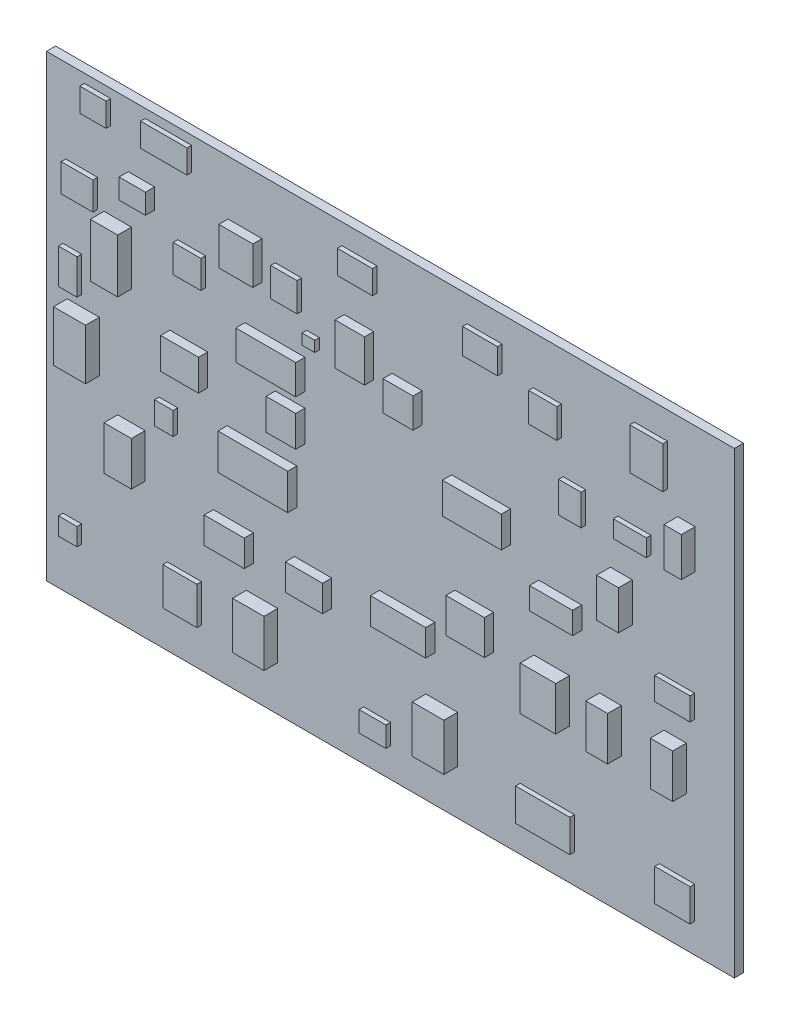
SolidWorks part; units mm, degrees
ref_plane "Front" through (0, 0, 0) normal (0, 0, 1) x (1, 0, 0)
ref_plane "Top" through (0, 0, 0) normal (0, 1, 0) x (1, 0, 0)
ref_plane "Right" through (0, 0, 0) normal (1, 0, 0) x (0, 0, -1)
sketch "Sketch1" plane through (0, 0, 0) normal (0, 0, 1) x (1, 0, 0)
  line L1 (-750, 500) -> (750, 500)
  line L2 (-750, 500) -> (-750, -500)
  line L3 (-750, -500) -> (750, -500)
  line L4 (750, 500) -> (750, -500)
  line L5 (-750, 500) -> (750, -500) construction
  line L6 (-750, -500) -> (750, 500) construction
  point P0 (0, 0)
  dimension "D1" = 1000
  dimension "D2" = 1500
extrude "Boss-Extrude1" add sketch "Sketch1" along normal blind 20
sketch "Sketch3" plane through (0, 0, 20) normal (0, 0, 1) x (1, 0, 0)
  line L1 (-317.0383, 203.9602) -> (-186.4548, 203.9602)
  line L2 (-317.0383, 203.9602) -> (-317.0383, 139.0841)
  line L3 (-317.0383, 139.0841) -> (-186.4548, 139.0841)
  line L4 (-186.4548, 203.9602) -> (-186.4548, 139.0841)
  line L5 (-317.0383, 203.9602) -> (-186.4548, 139.0841) construction
  line L6 (-317.0383, 139.0841) -> (-186.4548, 203.9602) construction
  line L7 (-355.9265, -9.9808) -> (-204.0397, -9.9808)
  line L8 (-355.9265, -9.9808) -> (-355.9265, -88.3609)
  line L9 (-355.9265, -88.3609) -> (-204.0397, -88.3609)
  line L10 (-204.0397, -9.9808) -> (-204.0397, -88.3609)
  line L11 (-355.9265, -9.9808) -> (-204.0397, -88.3609) construction
  line L12 (-355.9265, -88.3609) -> (-204.0397, -9.9808) construction
  line L13 (-571.6187, 361.8722) -> (-514.0837, 361.8722)
  line L14 (-571.6187, 361.8722) -> (-571.6187, 318.1665)
  line L15 (-571.6187, 318.1665) -> (-514.0837, 318.1665)
  line L16 (-514.0837, 361.8722) -> (-514.0837, 318.1665)
  line L17 (-571.6187, 361.8722) -> (-514.0837, 318.1665) construction
  line L18 (-571.6187, 318.1665) -> (-514.0837, 361.8722) construction
  line L19 (-354.0935, 381.1909) -> (-279.9831, 381.1909)
  line L20 (-354.0935, 381.1909) -> (-354.0935, 298.8478)
  line L21 (-354.0935, 298.8478) -> (-279.9831, 298.8478)
  line L22 (-279.9831, 381.1909) -> (-279.9831, 298.8478)
  line L23 (-354.0935, 381.1909) -> (-279.9831, 298.8478) construction
  line L24 (-354.0935, 298.8478) -> (-279.9831, 381.1909) construction
  line L25 (-251.1089, 107.9296) -> (-186.4548, 107.9296)
  line L26 (-251.1089, 107.9296) -> (-251.1089, 40.1021)
  line L27 (-251.1089, 40.1021) -> (-186.4548, 40.1021)
  line L28 (-186.4548, 107.9296) -> (-186.4548, 40.1021)
  line L29 (-251.1089, 107.9296) -> (-186.4548, 40.1021) construction
  line L30 (-251.1089, 40.1021) -> (-186.4548, 107.9296) construction
  line L31 (-100.7834, 327.4037) -> (-36.4863, 327.4037)
  line L32 (-100.7834, 327.4037) -> (-100.7834, 236.3285)
  line L33 (-100.7834, 236.3285) -> (-36.4863, 236.3285)
  line L34 (-36.4863, 327.4037) -> (-36.4863, 236.3285)
  line L35 (-100.7834, 327.4037) -> (-36.4863, 236.3285) construction
  line L36 (-100.7834, 236.3285) -> (-36.4863, 327.4037) construction
  line L37 (3.7883, 268.6967) -> (69.2703, 268.6967)
  line L38 (3.7883, 268.6967) -> (3.7883, 203.9602)
  line L39 (3.7883, 203.9602) -> (69.2703, 203.9602)
  line L40 (69.2703, 268.6967) -> (69.2703, 203.9602)
  line L41 (3.7883, 268.6967) -> (69.2703, 203.9602) construction
  line L42 (3.7883, 203.9602) -> (69.2703, 268.6967) construction
  line L43 (-480.9938, 107.9296) -> (-398.4458, 107.9296)
  line L44 (-480.9938, 107.9296) -> (-480.9938, 40.1021)
  line L45 (-480.9938, 40.1021) -> (-398.4458, 40.1021)
  line L46 (-398.4458, 107.9296) -> (-398.4458, 40.1021)
  line L47 (-480.9938, 107.9296) -> (-398.4458, 40.1021) construction
  line L48 (-480.9938, 40.1021) -> (-398.4458, 107.9296) construction
  line L49 (-386.1582, -183.6237) -> (-298.6708, -183.6237)
  line L50 (-386.1582, -183.6237) -> (-386.1582, -241.3069)
  line L51 (-386.1582, -241.3069) -> (-298.6708, -241.3069)
  line L52 (-298.6708, -183.6237) -> (-298.6708, -241.3069)
  line L53 (-386.1582, -183.6237) -> (-298.6708, -241.3069) construction
  line L54 (-386.1582, -241.3069) -> (-298.6708, -183.6237) construction
  line L55 (-209.0077, -183.6237) -> (-128.0535, -183.6237)
  line L56 (-209.0077, -183.6237) -> (-209.0077, -241.3069)
  line L57 (-209.0077, -241.3069) -> (-128.0535, -241.3069)
  line L58 (-128.0535, -183.6237) -> (-128.0535, -241.3069)
  line L59 (-209.0077, -183.6237) -> (-128.0535, -241.3069) construction
  line L60 (-209.0077, -241.3069) -> (-128.0535, -183.6237) construction
  line L61 (-23.8058, -154.7821) -> (96.8644, -154.7821)
  line L62 (-23.8058, -154.7821) -> (-23.8058, -212.4653)
  line L63 (-23.8058, -212.4653) -> (96.8644, -212.4653)
  line L64 (96.8644, -154.7821) -> (96.8644, -212.4653)
  line L65 (-23.8058, -154.7821) -> (96.8644, -212.4653) construction
  line L66 (-23.8058, -212.4653) -> (96.8644, -154.7821) construction
  line L67 (140.84, -72.08) -> (224.8272, -72.08)
  line L68 (140.84, -72.08) -> (140.84, -147.6702)
  line L69 (140.84, -147.6702) -> (224.8272, -147.6702)
  line L70 (224.8272, -72.08) -> (224.8272, -147.6702)
  line L71 (140.84, -72.08) -> (224.8272, -147.6702) construction
  line L72 (140.84, -147.6702) -> (224.8272, -72.08) construction
  line L73 (133.3998, 141.8434) -> (261.7349, 141.8434)
  line L74 (133.3998, 141.8434) -> (133.3998, 74.0159)
  line L75 (133.3998, 74.0159) -> (261.7349, 74.0159)
  line L76 (261.7349, 141.8434) -> (261.7349, 74.0159)
  line L77 (133.3998, 141.8434) -> (261.7349, 74.0159) construction
  line L78 (133.3998, 74.0159) -> (261.7349, 141.8434) construction
  line L79 (323.3608, 37.9257) -> (417.2566, 37.9257)
  line L80 (323.3608, 37.9257) -> (323.3608, -9.9808)
  line L81 (323.3608, -9.9808) -> (417.2566, -9.9808)
  line L82 (417.2566, 37.9257) -> (417.2566, -9.9808)
  line L83 (323.3608, 37.9257) -> (417.2566, -9.9808) construction
  line L84 (323.3608, -9.9808) -> (417.2566, 37.9257) construction
  point P0 (-251.7466, 171.5221)
  point P5 (-279.9831, -49.1709)
  point P10 (-542.8512, 340.0193)
  point P15 (-317.0383, 340.0193)
  point P20 (-218.7819, 74.0159)
  point P25 (-68.6349, 281.8661)
  point P30 (36.5293, 236.3285)
  point P35 (-439.7198, 74.0159)
  point P40 (-342.4145, -212.4653)
  point P45 (-168.5306, -212.4653)
  point P50 (36.5293, -183.6237)
  point P55 (182.8336, -109.8751)
  point P60 (197.5674, 107.9296)
  point P65 (370.3087, 13.9724)
extrude "Boss-Extrude3" add sketch "Sketch3" along normal blind 20
sketch "Sketch4" plane through (0, 0, 20) normal (0, 0, 1) x (1, 0, 0)
  line L1 (-463.823, 287.2753) -> (-403.3178, 287.2753)
  line L2 (-463.823, 287.2753) -> (-463.823, 226.4325)
  line L3 (-463.823, 226.4325) -> (-403.3178, 226.4325)
  line L4 (-403.3178, 287.2753) -> (-403.3178, 226.4325)
  line L5 (-463.823, 287.2753) -> (-403.3178, 226.4325) construction
  line L6 (-463.823, 226.4325) -> (-403.3178, 287.2753) construction
  line L7 (-105.8832, 455.092) -> (-29.1701, 455.092)
  line L8 (-105.8832, 455.092) -> (-105.8832, 403.7369)
  line L9 (-105.8832, 403.7369) -> (-29.1701, 403.7369)
  line L10 (-29.1701, 455.092) -> (-29.1701, 403.7369)
  line L11 (-105.8832, 455.092) -> (-29.1701, 403.7369) construction
  line L12 (-105.8832, 403.7369) -> (-29.1701, 455.092) construction
  line L13 (-251.2508, 350.1229) -> (-193.5545, 350.1229)
  line L14 (-251.2508, 350.1229) -> (-251.2508, 287.2753)
  line L15 (-251.2508, 287.2753) -> (-193.5545, 287.2753)
  line L16 (-193.5545, 350.1229) -> (-193.5545, 287.2753)
  line L17 (-251.2508, 350.1229) -> (-193.5545, 287.2753) construction
  line L18 (-251.2508, 287.2753) -> (-193.5545, 350.1229) construction
  line L19 (167.2364, 444.0695) -> (243.4631, 444.0695)
  line L20 (167.2364, 444.0695) -> (167.2364, 388.8199)
  line L21 (167.2364, 388.8199) -> (243.4631, 388.8199)
  line L22 (243.4631, 444.0695) -> (243.4631, 388.8199)
  line L23 (167.2364, 444.0695) -> (243.4631, 388.8199) construction
  line L24 (167.2364, 388.8199) -> (243.4631, 444.0695) construction
  line L25 (311.388, 395.4244) -> (372.7703, 395.4244)
  line L26 (311.388, 395.4244) -> (311.388, 331.6449)
  line L27 (311.388, 331.6449) -> (372.7703, 331.6449)
  line L28 (372.7703, 395.4244) -> (372.7703, 331.6449)
  line L29 (311.388, 395.4244) -> (372.7703, 331.6449) construction
  line L30 (311.388, 331.6449) -> (372.7703, 395.4244) construction
  line L31 (531.9625, 440.7258) -> (603.8475, 440.7258)
  line L32 (531.9625, 440.7258) -> (531.9625, 350.1229)
  line L33 (531.9625, 350.1229) -> (603.8475, 350.1229)
  line L34 (603.8475, 440.7258) -> (603.8475, 350.1229)
  line L35 (531.9625, 440.7258) -> (603.8475, 350.1229) construction
  line L36 (531.9625, 350.1229) -> (603.8475, 440.7258) construction
  line L37 (496.0199, 245.2414) -> (567.905, 245.2414)
  line L38 (496.0199, 245.2414) -> (496.0199, 207.6237)
  line L39 (496.0199, 207.6237) -> (567.905, 207.6237)
  line L40 (567.905, 245.2414) -> (567.905, 207.6237)
  line L41 (496.0199, 245.2414) -> (567.905, 207.6237) construction
  line L42 (496.0199, 207.6237) -> (567.905, 245.2414) construction
  line L43 (376.7873, 260.125) -> (425.6283, 260.125)
  line L44 (376.7873, 260.125) -> (376.7873, 192.74)
  line L45 (376.7873, 192.74) -> (425.6283, 192.74)
  line L46 (425.6283, 260.125) -> (425.6283, 192.74)
  line L47 (376.7873, 260.125) -> (425.6283, 192.74) construction
  line L48 (376.7873, 192.74) -> (425.6283, 260.125) construction
  line L49 (-504.3705, -30.1978) -> (-463.823, -30.1978)
  line L50 (-504.3705, -30.1978) -> (-504.3705, -79.5906)
  line L51 (-504.3705, -79.5906) -> (-463.823, -79.5906)
  line L52 (-463.823, -30.1978) -> (-463.823, -79.5906)
  line L53 (-504.3705, -30.1978) -> (-463.823, -79.5906) construction
  line L54 (-504.3705, -79.5906) -> (-463.823, -30.1978) construction
  line L55 (-708.0551, 317.6968) -> (-638.6656, 317.6968)
  line L56 (-708.0551, 317.6968) -> (-708.0551, 256.8539)
  line L57 (-708.0551, 256.8539) -> (-638.6656, 256.8539)
  line L58 (-638.6656, 317.6968) -> (-638.6656, 256.8539)
  line L59 (-708.0551, 317.6968) -> (-638.6656, 256.8539) construction
  line L60 (-708.0551, 256.8539) -> (-638.6656, 317.6968) construction
  line L61 (-667.2335, 480.7695) -> (-610.0977, 480.7695)
  line L62 (-667.2335, 480.7695) -> (-667.2335, 429.4144)
  line L63 (-667.2335, 429.4144) -> (-610.0977, 429.4144)
  line L64 (-610.0977, 480.7695) -> (-610.0977, 429.4144)
  line L65 (-667.2335, 480.7695) -> (-610.0977, 429.4144) construction
  line L66 (-667.2335, 429.4144) -> (-610.0977, 480.7695) construction
  line L67 (-534.6232, 480.7695) -> (-433.5704, 480.7695)
  line L68 (-534.6232, 480.7695) -> (-534.6232, 429.4144)
  line L69 (-534.6232, 429.4144) -> (-433.5704, 429.4144)
  line L70 (-433.5704, 480.7695) -> (-433.5704, 429.4144)
  line L71 (-534.6232, 480.7695) -> (-433.5704, 429.4144) construction
  line L72 (-534.6232, 429.4144) -> (-433.5704, 480.7695) construction
  line L73 (-713.8763, 155.3115) -> (-673.3604, 155.3115)
  line L74 (-713.8763, 155.3115) -> (-713.8763, 78.9005)
  line L75 (-713.8763, 78.9005) -> (-673.3604, 78.9005)
  line L76 (-673.3604, 155.3115) -> (-673.3604, 78.9005)
  line L77 (-713.8763, 155.3115) -> (-673.3604, 78.9005) construction
  line L78 (-713.8763, 78.9005) -> (-673.3604, 155.3115) construction
  line L79 (-713.8763, -354.1435) -> (-673.3604, -354.1435)
  line L80 (-713.8763, -354.1435) -> (-713.8763, -392.5928)
  line L81 (-713.8763, -392.5928) -> (-673.3604, -392.5928)
  line L82 (-673.3604, -354.1435) -> (-673.3604, -392.5928)
  line L83 (-713.8763, -354.1435) -> (-673.3604, -392.5928) construction
  line L84 (-713.8763, -392.5928) -> (-673.3604, -354.1435) construction
  line L85 (586.3863, -365.8902) -> (663.3344, -365.8902)
  line L86 (586.3863, -365.8902) -> (586.3863, -436.5313)
  line L87 (586.3863, -436.5313) -> (663.3344, -436.5313)
  line L88 (663.3344, -365.8902) -> (663.3344, -436.5313)
  line L89 (586.3863, -365.8902) -> (663.3344, -436.5313) construction
  line L90 (586.3863, -436.5313) -> (663.3344, -365.8902) construction
  line L91 (-58.3402, -392.1716) -> (0, -392.1716)
  line L92 (-58.3402, -392.1716) -> (-58.3402, -436.5313)
  line L93 (-58.3402, -436.5313) -> (0, -436.5313)
  line L94 (0, -392.1716) -> (0, -436.5313)
  line L95 (-58.3402, -392.1716) -> (0, -436.5313) construction
  line L96 (-58.3402, -436.5313) -> (0, -392.1716) construction
  line L97 (-486.1774, -332.3849) -> (-411.9629, -332.3849)
  line L98 (-486.1774, -332.3849) -> (-486.1774, -414.3515)
  line L99 (-486.1774, -414.3515) -> (-411.9629, -414.3515)
  line L100 (-411.9629, -332.3849) -> (-411.9629, -414.3515)
  line L101 (-486.1774, -332.3849) -> (-411.9629, -414.3515) construction
  line L102 (-486.1774, -414.3515) -> (-411.9629, -332.3849) construction
  line L103 (282.9505, -365.8902) -> (401.2078, -365.8902)
  line L104 (282.9505, -365.8902) -> (282.9505, -436.5313)
  line L105 (282.9505, -436.5313) -> (401.2078, -436.5313)
  line L106 (401.2078, -365.8902) -> (401.2078, -436.5313)
  line L107 (282.9505, -365.8902) -> (401.2078, -436.5313) construction
  line L108 (282.9505, -436.5313) -> (401.2078, -365.8902) construction
  line L109 (586.3863, -5.5014) -> (663.3344, -5.5014)
  line L110 (586.3863, -5.5014) -> (586.3863, -54.8942)
  line L111 (586.3863, -54.8942) -> (663.3344, -54.8942)
  line L112 (663.3344, -5.5014) -> (663.3344, -54.8942)
  line L113 (586.3863, -5.5014) -> (663.3344, -54.8942) construction
  line L114 (586.3863, -54.8942) -> (663.3344, -5.5014) construction
  line L115 (-182.6547, 233.6288) -> (-155.0357, 233.6288)
  line L116 (-182.6547, 233.6288) -> (-182.6547, 256.8539)
  line L117 (-182.6547, 256.8539) -> (-155.0357, 256.8539)
  line L118 (-155.0357, 233.6288) -> (-155.0357, 256.8539)
  line L119 (-182.6547, 233.6288) -> (-155.0357, 256.8539) construction
  line L120 (-182.6547, 256.8539) -> (-155.0357, 233.6288) construction
  point P0 (-433.5704, 256.8539)
  point P5 (-67.5266, 429.4144)
  point P10 (-222.4026, 318.6991)
  point P15 (205.3498, 416.4447)
  point P20 (342.0792, 363.5347)
  point P25 (567.905, 395.4244)
  point P30 (531.9625, 226.4325)
  point P35 (401.2078, 226.4325)
  point P40 (-484.0968, -54.8942)
  point P45 (-673.3604, 287.2753)
  point P50 (-638.6656, 455.092)
  point P55 (-484.0968, 455.092)
  point P60 (-693.6183, 117.106)
  point P65 (-693.6183, -373.3682)
  point P70 (624.8604, -401.2108)
  point P75 (-29.1701, -414.3515)
  point P80 (-449.0701, -373.3682)
  point P85 (342.0792, -401.2108)
  point P90 (624.8604, -30.1978)
  point P95 (-168.8452, 245.2414)
extrude "Boss-Extrude4" add sketch "Sketch4" along normal blind 10
sketch "Sketch5" plane through (0, 0, 20) normal (0, 0, 1) x (1, 0, 0)
  line L1 (-704.6332, 55.3522) -> (-634.7464, 55.3522)
  line L2 (-704.6332, 55.3522) -> (-704.6332, -55.3522)
  line L3 (-704.6332, -55.3522) -> (-634.7464, -55.3522)
  line L4 (-634.7464, 55.3522) -> (-634.7464, -55.3522)
  line L5 (-704.6332, 55.3522) -> (-634.7464, -55.3522) construction
  line L6 (-704.6332, -55.3522) -> (-634.7464, 55.3522) construction
  line L7 (-624.4947, 260.6451) -> (-564.7182, 260.6451)
  line L8 (-624.4947, 260.6451) -> (-624.4947, 143.6794)
  line L9 (-624.4947, 143.6794) -> (-564.7182, 143.6794)
  line L10 (-564.7182, 260.6451) -> (-564.7182, 143.6794)
  line L11 (-624.4947, 260.6451) -> (-564.7182, 143.6794) construction
  line L12 (-624.4947, 143.6794) -> (-564.7182, 260.6451) construction
  line L13 (-534.83, -108.7082) -> (-594.6064, -108.7082)
  line L14 (-534.83, -108.7082) -> (-534.83, -204.1898)
  line L15 (-534.83, -204.1898) -> (-594.6064, -204.1898)
  line L16 (-594.6064, -108.7082) -> (-594.6064, -204.1898)
  line L17 (-534.83, -108.7082) -> (-594.6064, -204.1898) construction
  line L18 (-534.83, -204.1898) -> (-594.6064, -108.7082) construction
  line L19 (312.897, -108.7082) -> (390.4968, -108.7082)
  line L20 (312.897, -108.7082) -> (312.897, -204.1898)
  line L21 (312.897, -204.1898) -> (390.4968, -204.1898)
  line L22 (390.4968, -108.7082) -> (390.4968, -204.1898)
  line L23 (312.897, -108.7082) -> (390.4968, -204.1898) construction
  line L24 (312.897, -204.1898) -> (390.4968, -108.7082) construction
  line L25 (77.5787, -299.9561) -> (146.5667, -299.9561)
  line L26 (77.5787, -299.9561) -> (77.5787, -402.4366)
  line L27 (77.5787, -402.4366) -> (146.5667, -402.4366)
  line L28 (146.5667, -299.9561) -> (146.5667, -402.4366)
  line L29 (77.5787, -299.9561) -> (146.5667, -402.4366) construction
  line L30 (77.5787, -402.4366) -> (146.5667, -299.9561) construction
  line L31 (-314.1466, -299.9561) -> (-245.6973, -299.9561)
  line L32 (-314.1466, -299.9561) -> (-314.1466, -402.4366)
  line L33 (-314.1466, -402.4366) -> (-245.6973, -402.4366)
  line L34 (-245.6973, -299.9561) -> (-245.6973, -402.4366)
  line L35 (-314.1466, -299.9561) -> (-245.6973, -402.4366) construction
  line L36 (-314.1466, -402.4366) -> (-245.6973, -299.9561) construction
  line L37 (479.7609, 140.655) -> (527.339, 140.655)
  line L38 (479.7609, 140.655) -> (479.7609, 55.3522)
  line L39 (479.7609, 55.3522) -> (527.339, 55.3522)
  line L40 (527.339, 140.655) -> (527.339, 55.3522)
  line L41 (479.7609, 140.655) -> (527.339, 55.3522) construction
  line L42 (479.7609, 55.3522) -> (527.339, 140.655) construction
  line L43 (455.9719, -108.7082) -> (503.55, -108.7082)
  line L44 (455.9719, -108.7082) -> (455.9719, -204.1898)
  line L45 (455.9719, -204.1898) -> (503.55, -204.1898)
  line L46 (503.55, -108.7082) -> (503.55, -204.1898)
  line L47 (455.9719, -108.7082) -> (503.55, -204.1898) construction
  line L48 (455.9719, -204.1898) -> (503.55, -108.7082) construction
  line L49 (596.7008, -108.7082) -> (645.3838, -108.7082)
  line L50 (596.7008, -108.7082) -> (596.7008, -204.1898)
  line L51 (596.7008, -204.1898) -> (645.3838, -204.1898)
  line L52 (645.3838, -108.7082) -> (645.3838, -204.1898)
  line L53 (596.7008, -108.7082) -> (645.3838, -204.1898) construction
  line L54 (596.7008, -204.1898) -> (645.3838, -108.7082) construction
  line L55 (626.3927, 309.4517) -> (664.3749, 309.4517)
  line L56 (626.3927, 309.4517) -> (626.3927, 224.2235)
  line L57 (626.3927, 224.2235) -> (664.3749, 224.2235)
  line L58 (664.3749, 309.4517) -> (664.3749, 224.2235)
  line L59 (626.3927, 309.4517) -> (664.3749, 224.2235) construction
  line L60 (626.3927, 224.2235) -> (664.3749, 309.4517) construction
  point P0 (-669.6898, 0)
  point P5 (-594.6064, 202.1622)
  point P10 (-564.7182, -156.449)
  point P15 (351.6969, -156.449)
  point P20 (112.0727, -351.1964)
  point P25 (-279.922, -351.1964)
  point P30 (503.55, 98.0036)
  point P35 (479.7609, -156.449)
  point P40 (621.0423, -156.449)
  point P45 (645.3838, 266.8376)
extrude "Boss-Extrude5" add sketch "Sketch5" along normal blind 30
